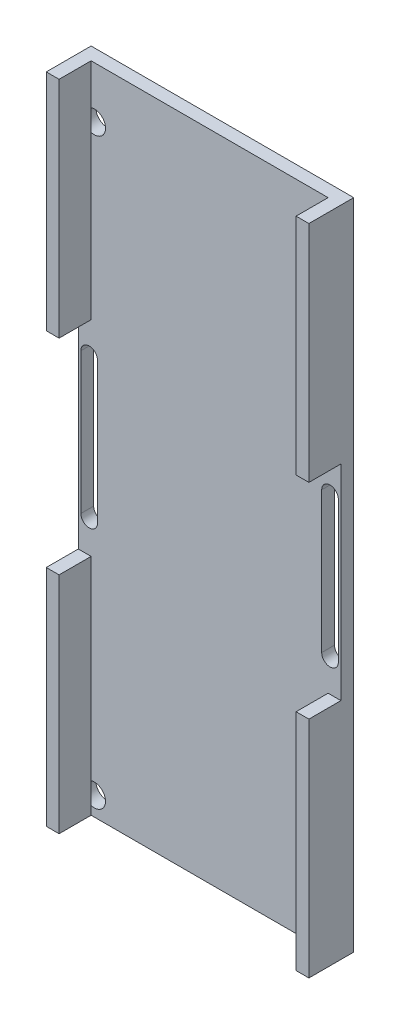
SolidWorks part; units mm, degrees
ref_plane "Front Plane" through (0, 0, 0) normal (0, 0, 1) x (1, 0, 0)
ref_plane "Top Plane" through (0, 0, 0) normal (0, 1, 0) x (1, 0, 0)
ref_plane "Right Plane" through (0, 0, 0) normal (1, 0, 0) x (0, 0, -1)
sketch "Floor and strap guides profile" plane through (0, 0, 0) normal (0, 0, 1) x (1, 0, 0)
  line L0 (-20.5, -51) -> (20.5, -51)
  line L1 (20.5, -51) -> (20.5, 51)
  line L2 (20.5, 51) -> (-20.5, 51)
  line L3 (-20.5, 51) -> (-20.5, -51)
  line L4 (-17.5, -11) -> (-17.5, 11)
  line L5 (-20.1, 11) -> (-20.1, -11)
  line L6 (20.1, -11) -> (20.1, 11)
  line L7 (17.5, 11) -> (17.5, -11)
  circle A0 centre (-18, -48) radius 1.75
  circle A1 centre (-18, 43) radius 1.75
  circle A2 centre (18, -48) radius 1.75
  circle A3 centre (18, 43) radius 1.75
  arc A4 (-17.5, 11) -> (-20.1, 11) centre (-18.8, 11) ccw
  arc A5 (-20.1, -11) -> (-17.5, -11) centre (-18.8, -11) ccw
  arc A6 (20.1, 11) -> (17.5, 11) centre (18.8, 11) ccw
  arc A7 (17.5, -11) -> (20.1, -11) centre (18.8, -11) ccw
extrude "Floor and strap guides" add sketch "Floor and strap guides profile" along normal blind 2
sketch "Integral edge stops profile" plane through (0, 0, 0) normal (0, 0, 1) x (1, 0, 0)
  line L0 (-20.5, -51) -> (-18.5, -51)
  line L1 (-18.5, -51) -> (-18.5, -16)
  line L2 (-18.5, -16) -> (-20.5, -16)
  line L3 (-20.5, -16) -> (-20.5, -51)
  line L4 (18.5, -51) -> (20.5, -51)
  line L5 (20.5, -51) -> (20.5, -16)
  line L6 (20.5, -16) -> (18.5, -16)
  line L7 (18.5, -16) -> (18.5, -51)
  line L8 (-20.5, 16) -> (-18.5, 16)
  line L9 (-18.5, 16) -> (-18.5, 51)
  line L10 (-18.5, 51) -> (-20.5, 51)
  line L11 (-20.5, 51) -> (-20.5, 16)
  line L12 (18.5, 16) -> (20.5, 16)
  line L13 (20.5, 16) -> (20.5, 51)
  line L14 (20.5, 51) -> (18.5, 51)
  line L15 (18.5, 51) -> (18.5, 16)
extrude "Integral edge stops" add sketch "Integral edge stops profile" along normal blind 5 from offset 2
